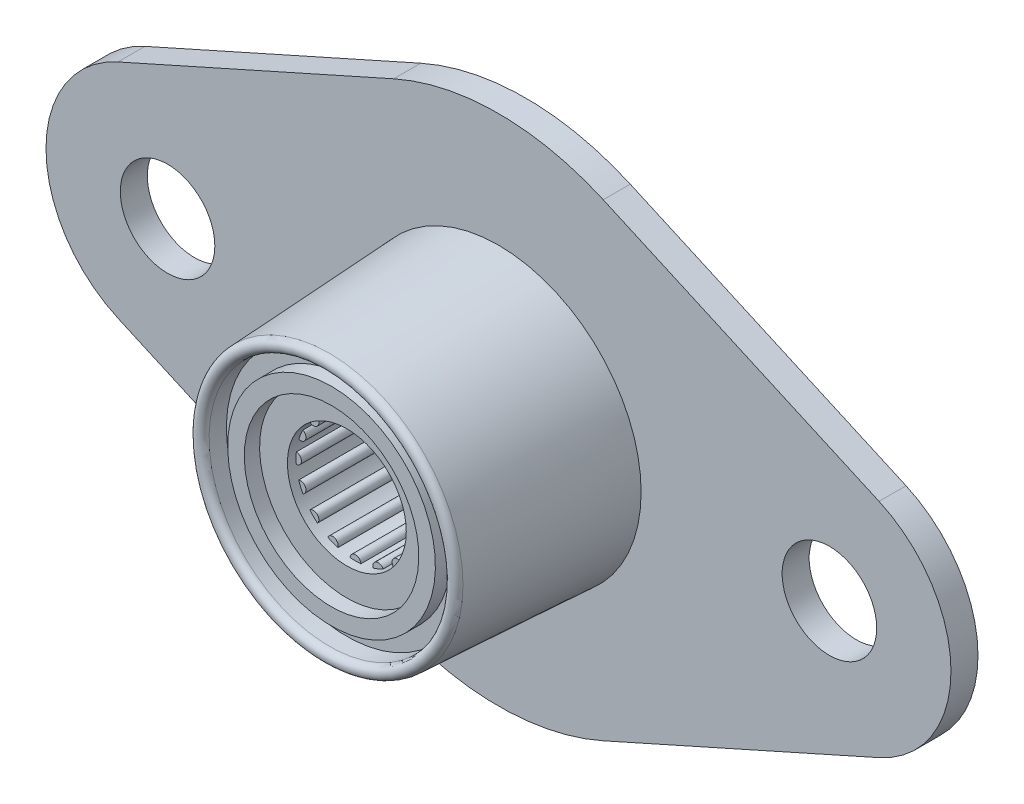
SolidWorks part; units mm, degrees
ref_plane "Front" through (0, 0, 0) normal (0, 0, 1) x (1, 0, 0)
ref_plane "Top" through (0, 0, 0) normal (0, 1, 0) x (1, 0, 0)
ref_plane "Right" through (0, 0, 0) normal (1, 0, 0) x (0, 0, -1)
sketch "Sketch1" plane through (0, 0, 0) normal (0, 0, 1) x (1, 0, 0)
  line L0 (0, 0) -> (-19.4469, 0) construction
  line L1 (0, 0) -> (19.4469, 0) construction
  line L2 (-22.3627, 6.5216) -> (-6.1556, 13.7678)
  line L3 (6.1556, 13.7678) -> (22.3627, 6.5216)
  line L4 (22.3627, -6.5216) -> (6.1556, -13.7678)
  line L5 (-6.1556, -13.7678) -> (-22.3627, -6.5216)
  line L6 (0, 15.0812) -> (0, -15.0812) construction
  arc A0 (6.1556, 13.7678) -> (-6.1556, 13.7678) centre (0, 0) ccw
  circle A1 centre (-19.4469, 0) radius 2.7781
  circle A2 centre (19.4469, 0) radius 2.7781
  arc A3 (22.3627, -6.5216) -> (22.3627, 6.5216) centre (19.4469, 0) ccw
  arc A4 (-22.3627, 6.5216) -> (-22.3627, -6.5216) centre (-19.4469, 0) ccw
  circle A5 centre (0, 0) radius 8.382
  arc A7 (-6.1556, -13.7678) -> (6.1556, -13.7678) centre (0, 0) ccw
  point P17 (0, 0)
  dimension "A" = 16.764
  dimension "Mounting Hole Dia" = 5.5562
  dimension "Overall Length" = 53.1812
  dimension "Mounting Holes" = 38.8937
  dimension "Overall Height" = 30.1625
extrude "Extrude1" add sketch "Sketch1" along normal blind 1.5875
sketch "Sketch2" plane through (0, 0, 0) normal (1, 0, 0) x (0, 0, -1)
  line L0 (0, 8.382) -> (-1.5875, 8.382)
  line L1 (-1.5875, 8.382) -> (-11.5356, 7.8606)
  line L2 (-11.5151, 7.079) -> (-10.4991, 7.079)
  line L3 (-10.4991, 7.079) -> (-10.4991, 6.103)
  line L4 (-10.4991, 3.175) -> (0, 3.175)
  line L5 (0, 3.175) -> (0, 8.382)
  line L6 (-10.4991, 6.103) -> (-11.3982, 6.103)
  line L7 (-11.3982, 6.103) -> (-11.3982, 5.127)
  line L8 (-11.3982, 5.127) -> (-10.4991, 5.127)
  line L9 (-10.4991, 6.103) -> (-10.4991, 5.127) construction
  line L10 (0, 0) -> (-10.4991, 0) construction
  line L11 (-10.4991, 0) -> (-10.4991, 3.175) construction
  line L12 (-10.4991, 4.151) -> (-10.4991, 3.175)
  line L13 (-10.4991, 5.127) -> (-10.4991, 4.151)
  line L14 (0, 13.7678) -> (0, 15.0813) construction
  line L15 (0, 13.7678) -> (0, 15.0813) construction
  line L16 (-11.5151, 7.4701) -> (-11.9062, 7.4701) construction
  arc A0 (-11.5356, 7.8606) -> (-11.9062, 7.4701) centre (-11.5151, 7.4701) ccw
  arc A1 (-11.9062, 7.4701) -> (-11.5151, 7.079) centre (-11.5151, 7.4701) ccw
  dimension "F" = 11.9062
  dimension "Shaft Dia" = 6.35
  dimension "D3" = 0.7817
  dimension "D4" = 1.016
  dimension "D5" = 3
  dimension "D2" = 0.508
  dimension "D6" = 0.976
revolve "Revolve1" add sketch "Sketch2" angle 360 about L10
sketch "Sketch3" plane through (0, 0, 10.4991) normal (0, 0, 1) x (1, 0, 0)
  line L0 (0, 0) -> (3.4925, 0) construction
  arc A0 (-1.624, 3.0919) -> (-2.2351, 2.6836) centre (0, 0) ccw
  arc A1 (3.4781, 0.3172) -> (3.4781, -0.3172) centre (3.4925, 0) ccw
  circle A2 centre (0, 0) radius 3.175 construction
  arc A3 (3.3347, -1.038) -> (3.0919, -1.624) centre (3.2266, -1.3365) ccw
  arc A4 (2.6836, -2.2351) -> (2.2351, -2.6836) centre (2.4696, -2.4696) ccw
  arc A5 (1.624, -3.0919) -> (1.038, -3.3347) centre (1.3365, -3.2266) ccw
  arc A6 (0.3172, -3.4781) -> (-0.3172, -3.4781) centre (0, -3.4925) ccw
  arc A7 (-1.038, -3.3347) -> (-1.624, -3.0919) centre (-1.3365, -3.2266) ccw
  arc A8 (-2.2351, -2.6836) -> (-2.6836, -2.2351) centre (-2.4696, -2.4696) ccw
  arc A9 (-3.0919, -1.624) -> (-3.3347, -1.038) centre (-3.2266, -1.3365) ccw
  arc A10 (-3.4781, -0.3172) -> (-3.4781, 0.3172) centre (-3.4925, 0) ccw
  arc A11 (-3.3347, 1.038) -> (-3.0919, 1.624) centre (-3.2266, 1.3365) ccw
  arc A12 (-2.6836, 2.2351) -> (-2.2351, 2.6836) centre (-2.4696, 2.4696) ccw
  arc A13 (-1.624, 3.0919) -> (-1.038, 3.3347) centre (-1.3365, 3.2266) ccw
  arc A14 (-0.3172, 3.4781) -> (0.3172, 3.4781) centre (0, 3.4925) ccw
  arc A15 (1.038, 3.3347) -> (1.624, 3.0919) centre (1.3365, 3.2266) ccw
  arc A16 (2.2351, 2.6836) -> (2.6836, 2.2351) centre (2.4696, 2.4696) ccw
  arc A17 (3.0919, 1.624) -> (3.3347, 1.038) centre (3.2266, 1.3365) ccw
  arc A18 (-2.6836, 2.2351) -> (-3.0919, 1.624) centre (0, 0) ccw
  arc A19 (-3.3347, 1.038) -> (-3.4781, 0.3172) centre (0, 0) ccw
  arc A20 (-3.4781, -0.3172) -> (-3.3347, -1.038) centre (0, 0) ccw
  arc A21 (-3.0919, -1.624) -> (-2.6836, -2.2351) centre (0, 0) ccw
  arc A22 (-2.2351, -2.6836) -> (-1.624, -3.0919) centre (0, 0) ccw
  arc A23 (-1.038, -3.3347) -> (-0.3172, -3.4781) centre (0, 0) ccw
  arc A24 (0.3172, -3.4781) -> (1.038, -3.3347) centre (0, 0) ccw
  arc A25 (1.624, -3.0919) -> (2.2351, -2.6836) centre (0, 0) ccw
  arc A26 (2.6836, -2.2351) -> (3.0919, -1.624) centre (0, 0) ccw
  arc A27 (3.3347, -1.038) -> (3.4781, -0.3172) centre (0, 0) ccw
  arc A28 (3.4781, 0.3172) -> (3.3347, 1.038) centre (0, 0) ccw
  arc A29 (3.0919, 1.624) -> (2.6836, 2.2351) centre (0, 0) ccw
  arc A30 (2.2351, 2.6836) -> (1.624, 3.0919) centre (0, 0) ccw
  arc A31 (1.038, 3.3347) -> (0.3172, 3.4781) centre (0, 0) ccw
  arc A32 (-0.3172, 3.4781) -> (-1.038, 3.3347) centre (0, 0) ccw
  dimension "D1" = 6.985
extrude "Cut-Extrude2" cut sketch "Sketch3" against normal through all
sketch "Sketch4" plane through (0, 0, 10.4991) normal (0, 0, 1) x (1, 0, 0)
  circle A0 centre (0, 0) radius 3.4925
extrude "Cut-Extrude3" cut sketch "Sketch4" against normal blind 0.508
sketch "Sketch5" plane through (0, 0, 0) normal (0, 0, -1) x (-1, 0, 0)
  circle A0 centre (0, 0) radius 3.4925
  arc A1 (1.038, 3.3347) -> (0.3172, 3.4781) centre (0, 0) ccw construction
extrude "Cut-Extrude4" cut sketch "Sketch5" against normal blind 0.508
equation "\"D1@Sketch3\"=\"Shaft Dia@Sketch2\"*1.1"
equation "\"D3@Sketch2\"=\"D6@Sketch2\"/1.25"
